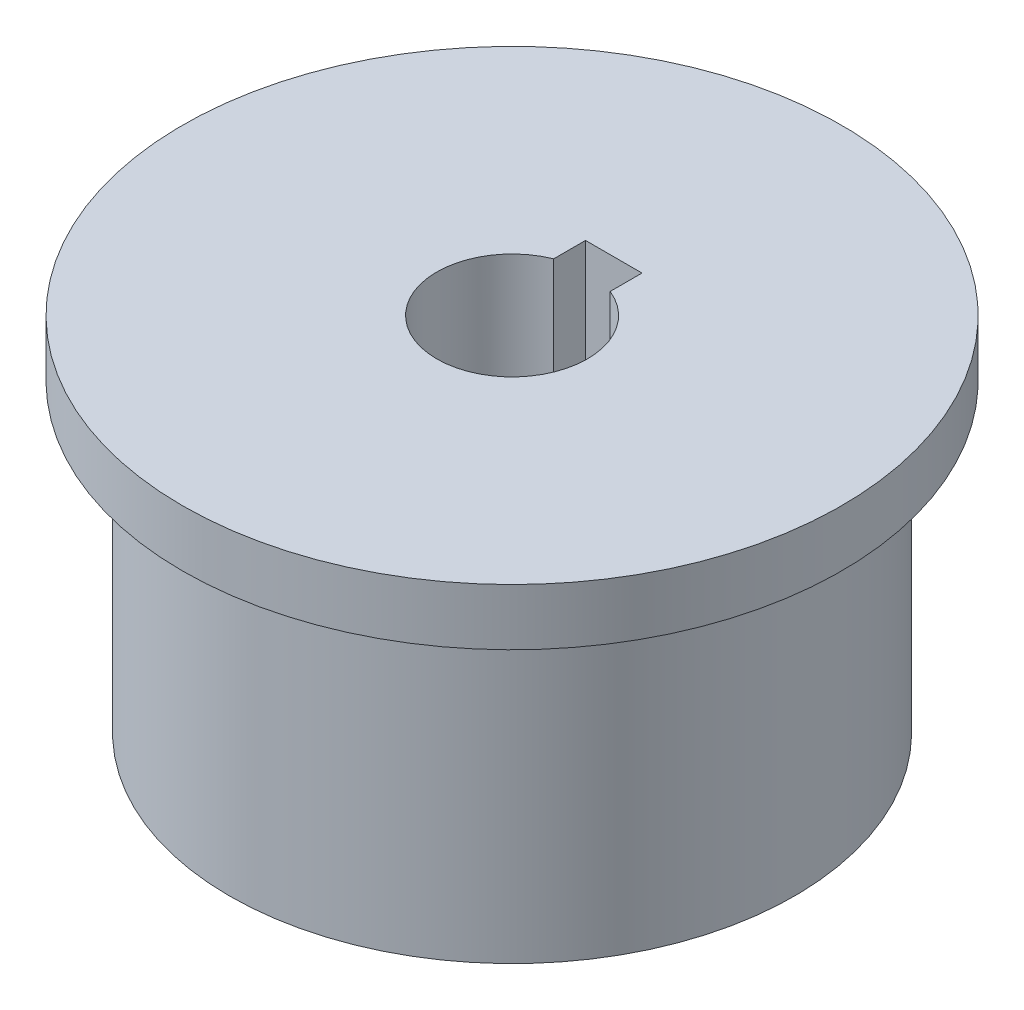
SolidWorks part; units mm, degrees
material "Alumina"
ref_plane "Plan de face" through (0, 0, 0) normal (0, 0, 1) x (1, 0, 0)
ref_plane "Plan de dessus" through (0, 0, 0) normal (0, 1, 0) x (1, 0, 0)
ref_plane "Plan de droite" through (0, 0, 0) normal (1, 0, 0) x (0, 0, -1)
sketch "Sketch1" plane through (0, 0, 0) normal (0, 0, 1) x (1, 0, 0)
  line L0 (0, 12.7093) -> (0, -8.2237) construction
  line L1 (4, 19.2) -> (17.5, 19.2)
  line L2 (17.5, 19.2) -> (17.5, 16.2)
  line L3 (17.5, 16.2) -> (15, 16.2)
  line L4 (15, 16.2) -> (15, 0)
  line L14 (4, -4) -> (4, 19.2)
  line L15 (4, -4) -> (5, -4)
  line L17 (15, 0) -> (9, 0)
  line L20 (5, -4) -> (9, 0)
  point P9 (0, 0)
  dimension "D1" = 16.2
  dimension "D2" = 3
  dimension "D3" = 17.5
  dimension "D4" = 15
  dimension "D7" = 1
  dimension "D8" = 45
  dimension "D9" = 8
  dimension "D10" = 4
revolve "Revolve1" add sketch "Sketch1" angle 360 about L0
sketch "Esquisse1" plane through (0, 19.2, 0) normal (0, 1, 0) x (1, 0, 0)
  line L0 (-1.5, 3.7081) -> (-1.5, 5.4)
  line L1 (-1.5, 5.4) -> (1.5, 5.4)
  line L2 (1.5, 5.4) -> (1.5, 3.7081)
  circle A1 centre (0, 0) radius 4 construction
  arc A2 (-1.5, 3.7081) -> (1.5, 3.7081) centre (0, 0) cw
  point P4 (0, 5.4)
  circle M2 centre (0, 0) radius 4
  dimension "D1" = 1.4
  dimension "D2" = 3
extrude "Enlèv. mat.-Extru.1" cut sketch "Esquisse1" against normal blind 16.5 contours L2 L1 L0 M2
